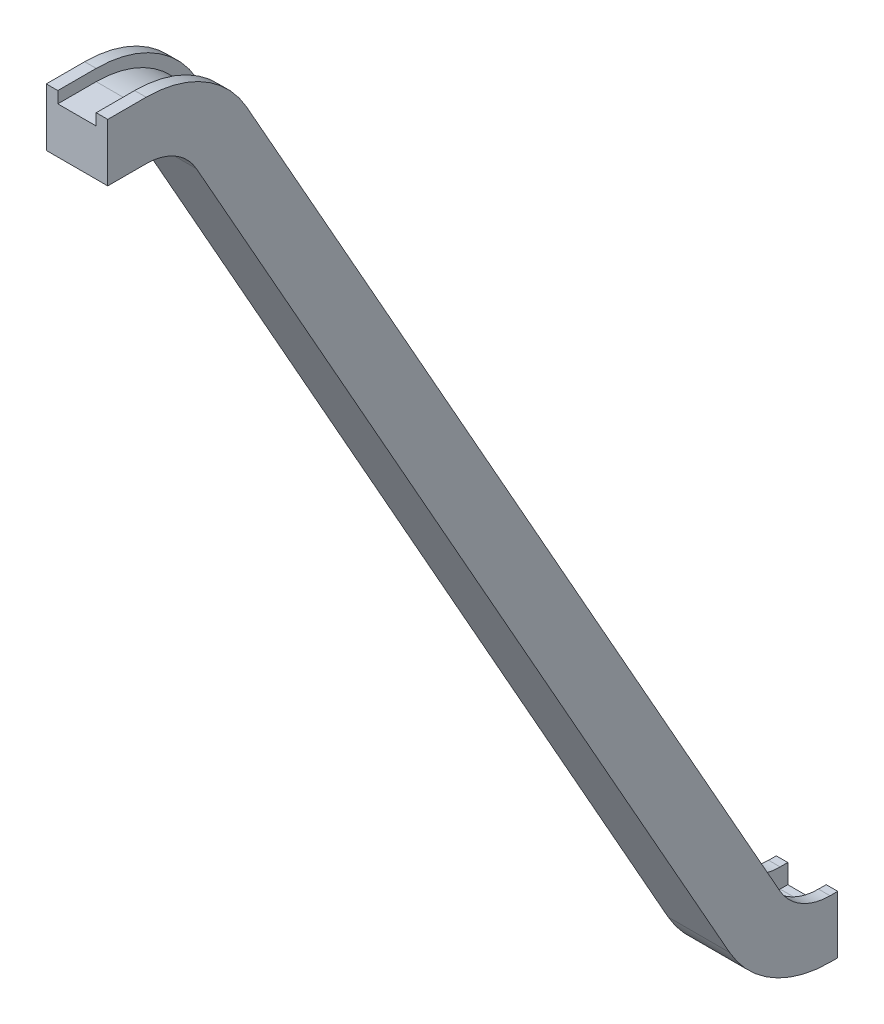
SolidWorks part; units mm, degrees
ref_plane "Front Plane" through (0, 0, 0) normal (0, 0, 1) x (1, 0, 0)
ref_plane "Top Plane" through (0, 0, 0) normal (0, 1, 0) x (1, 0, 0)
ref_plane "Right Plane" through (0, 0, 0) normal (1, 0, 0) x (0, 0, -1)
sketch "Sketch1" plane through (0, 0, 0) normal (1, 0, 0) x (0, 0, -1)
  line L0 (0, 0) -> (10, 0)
  line L1 (188, -269) -> (190, -269)
  line L2 (23.0652, -7.6312) -> (161.8695, -253.7376)
  line L3 (0, 0) -> (0, 15)
  line L4 (0, 15) -> (10, 15)
  line L5 (36.1305, -0.2624) -> (174.9348, -246.3688)
  line L6 (190, -269) -> (190, -254)
  line L7 (190, -254) -> (188, -254)
  circle A0 centre (10, -15) radius 15
  circle A1 centre (188, -239) radius 30
  circle A2 centre (10, -15) radius 30
  circle A3 centre (188, -239) radius 15
  dimension "D1" = 30
  dimension "D4" = 2
  dimension "D6" = 15
  dimension "D2" = 190
  dimension "D3" = 269
  dimension "D5" = 10
extrude "Boss-Extrude1" add sketch "Sketch1" along normal blind 16 contours A2 L2 A1 L5 | A3 L5 A1 L6 L7 | A2 L3 L0 A0 L2 | A2 L4 L3 | A1 L1 L6
sketch "Sketch3" plane through (16, 0, 0) normal (1, 0, 0) x (0, 0, -1)
  line L0 (0, 15) -> (10, 15)
  line L1 (0, 15) -> (0, 13.2843)
  line L2 (0, 0) -> (0, 15) construction
  line L3 (10, 12) -> (0, 12)
  line L4 (0, 13.2843) -> (0, 12)
  line L5 (188, -259) -> (190, -259)
  line L6 (190, -269) -> (190, -254) construction
  line L7 (188, -254) -> (190, -254)
  line L8 (190, -254) -> (190, -259)
  line L9 (170.5105, -248.7015) -> (33.6108, -1.903)
  line L10 (36.1305, -0.2624) -> (174.9348, -246.3688)
  circle A0 centre (10, -15) radius 30
  arc A1 (36.1305, -0.2624) -> (10, 15) centre (10, -15) ccw construction
  circle A2 centre (188, -239) radius 15
  arc A3 (174.9348, -246.3688) -> (188, -254) centre (188, -239) ccw construction
  circle A4 centre (188, -239) radius 20
  circle A5 centre (10, -15) radius 27
  line M6 (174.9348, -246.3688) -> (36.1305, -0.2624)
  arc M7 (36.1305, -0.2624) -> (10, 15) centre (10, -15) ccw
  line M8 (10, 15) -> (0, 15)
  line M9 (0, 15) -> (0, 0)
  line M15 (190, -269) -> (190, -254)
  line M16 (190, -254) -> (188, -254)
  arc M17 (188, -254) -> (174.9348, -246.3688) centre (188, -239) cw
  dimension "D1" = 3
  dimension "D2" = 5
extrude "Cut-Extrude1" cut sketch "Sketch3" against normal blind 10 from offset 3 contours A4 L7 M6 M17 | A4 L5 M15 M16 | A4 L10 A0 L9 | A5 L9 A0 L3 M7 M9 | A0 M8 M9
